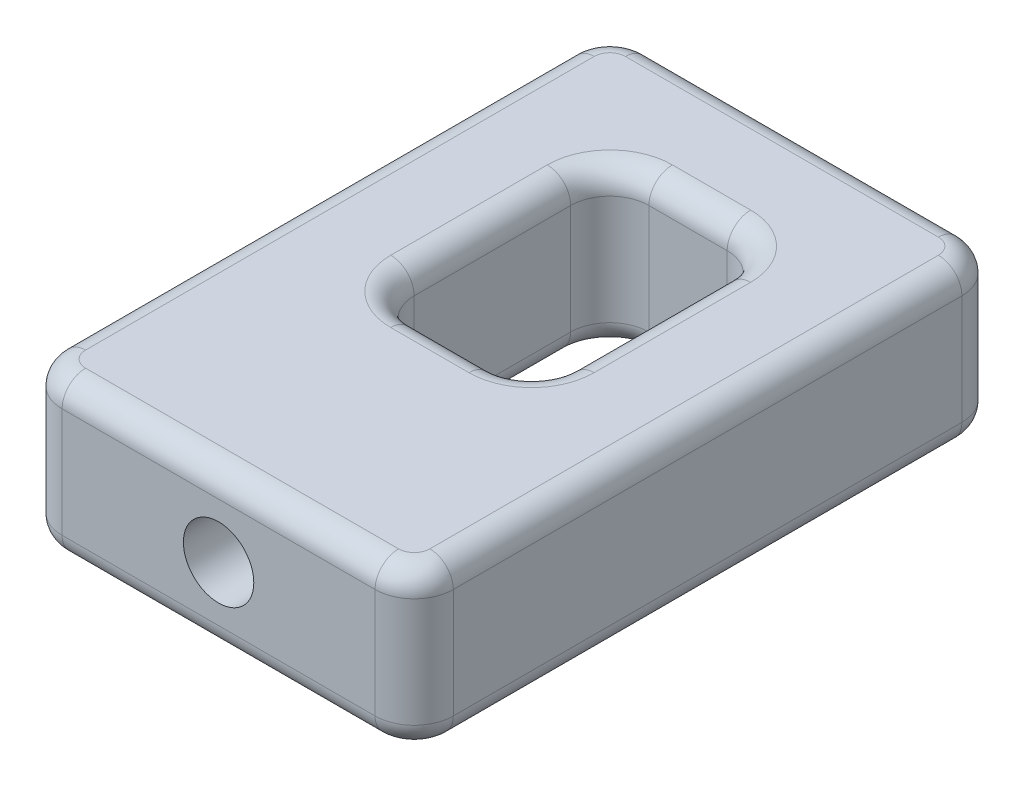
SolidWorks part; units mm, degrees
ref_plane "Front Plane" through (0, 0, 0) normal (0, 0, 1) x (1, 0, 0)
ref_plane "Top Plane" through (0, 0, 0) normal (0, 1, 0) x (1, 0, 0)
ref_plane "Right Plane" through (0, 0, 0) normal (1, 0, 0) x (0, 0, -1)
sketch "Sketch1" plane through (0, 0, 0) normal (0, 1, 0) x (1, 0, 0)
  line L1 (-6.35, 9.525) -> (6.35, 9.525)
  line L2 (-6.35, 9.525) -> (-6.35, -9.525)
  line L3 (-6.35, -9.525) -> (6.35, -9.525)
  line L4 (6.35, 9.525) -> (6.35, -9.525)
  line L5 (-6.35, 9.525) -> (6.35, -9.525) construction
  line L6 (-6.35, -9.525) -> (6.35, 9.525) construction
  point P0 (0, 0)
  dimension "D1" = 12.7
  dimension "D2" = 19.05
extrude "Boss-Extrude1" add sketch "Sketch1" along normal blind 5.08
sketch "Sketch2" plane through (0, 0, 0) normal (0, -1, 0) x (1, 0, 0)
  line L0 (6.35, -9.525) -> (-6.35, -9.525) construction
  line L1 (-2.54, -5.715) -> (2.54, -5.715)
  line L2 (-2.54, -5.715) -> (-2.54, 1.905)
  line L3 (-2.54, 1.905) -> (2.54, 1.905)
  line L4 (2.54, -5.715) -> (2.54, 1.905)
  line L5 (-2.54, -5.715) -> (2.54, 1.905) construction
  line L6 (-2.54, 1.905) -> (2.54, -5.715) construction
  line L7 (6.35, 9.525) -> (6.35, -9.525) construction
  line L8 (-6.35, -9.525) -> (-6.35, 9.525) construction
  line L9 (-6.35, 9.525) -> (6.35, 9.525) construction
  point P0 (0, -1.905)
  dimension "D1" = 3.81
  dimension "D2" = 3.81
  dimension "D3" = 3.81
  dimension "D4" = 7.62
extrude "Cut-Extrude1" cut sketch "Sketch2" against normal through all
sketch "Sketch3" plane through (0, 0, 9.525) normal (0, 0, 1) x (1, 0, 0)
  line L0 (0, 0) -> (0, 5.08) construction
  line L1 (-6.35, 5.08) -> (6.35, 5.08) construction
  line L2 (6.35, 2.54) -> (-6.35, 2.54) construction
  line L3 (6.35, 5.08) -> (6.35, 0) construction
  line L4 (-6.35, 5.08) -> (-6.35, 0) construction
  circle A0 centre (0, 2.54) radius 1.143
extrude "Cut-Extrude3" cut sketch "Sketch3" against normal blind 8.382
fillet "Fillet1" radius 1.27 4 edges at (6.35, 2.54, -9.525) (-6.35, 2.54, -9.525) (-6.35, 2.54, 9.525) (6.35, 2.54, 9.525)
fillet "Fillet2" radius 1.27 4 edges at (-2.54, 2.54, -5.715) (2.54, 2.54, -5.715) (-2.54, 2.54, 1.905) (2.54, 2.54, 1.905)
fillet "Fillet3" radius 0.762 8 edges at (5.978, 5.08, 9.153) (0, 5.08, 9.525) (-5.978, 5.08, 9.153) (-6.35, 5.08, 0) (-5.978, 5.08, -9.153) (0, 5.08, -9.525) (5.978, 5.08, -9.153) (6.35, 5.08, 0)
fillet "Fillet4" radius 0.762 24 edges at (2.168, 5.08, 1.533) (2.54, 5.08, -1.905) (2.168, 5.08, -5.343) (0, 5.08, -5.715) (-2.168, 5.08, -5.343) (-2.54, 5.08, -1.905) (-2.168, 5.08, 1.533) (2.168, 0, 1.533) (2.54, 0, -1.905) (2.168, 0, -5.343) (0, 0, -5.715) (-2.168, 0, -5.343) (-2.54, 0, -1.905) (-2.168, 0, 1.533) (-5.978, 0, -9.153) (0, 0, -9.525) (5.978, 0, -9.153) (6.35, 0, 0) (5.978, 0, 9.153) (0, 0, 9.525) (-5.978, 0, 9.153) (0, 5.08, 1.905) (0, 0, 1.905) (-6.35, 0, 0)
equation "\"D3@Sketch2\"=\"D2@Sketch2\""
equation "\"0..4in\"=0.3"
